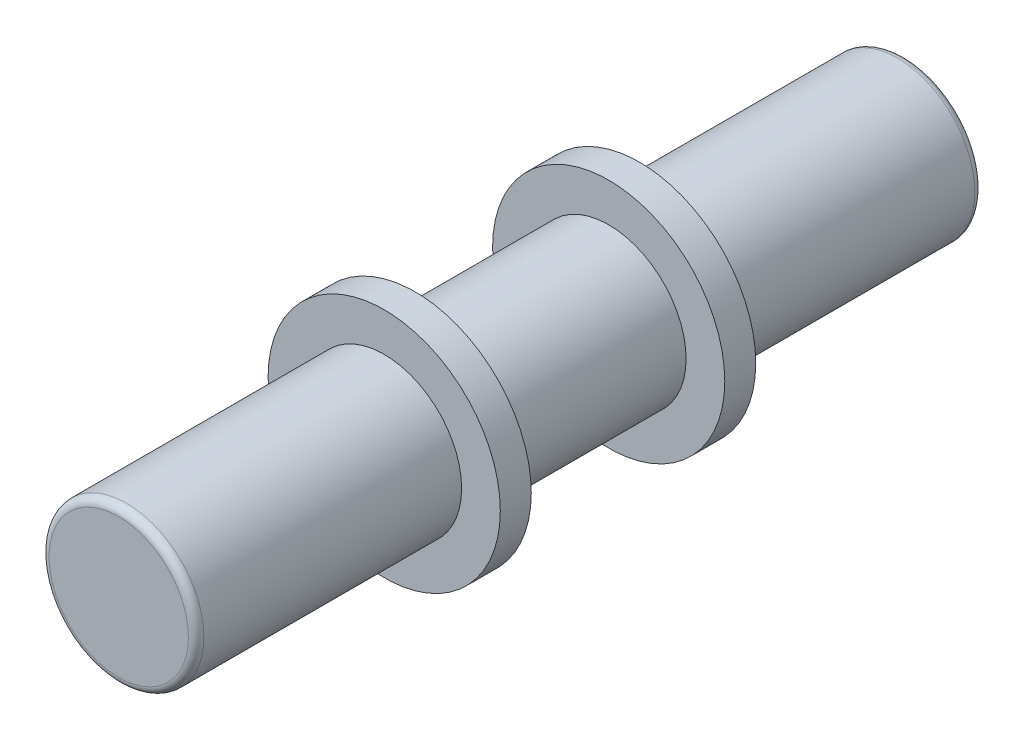
SolidWorks part; units mm, degrees
material "Plain Carbon Steel"
ref_plane "Front Plane" through (0, 0, 0) normal (0, 0, 1) x (1, 0, 0)
ref_plane "Top Plane" through (0, 0, 0) normal (0, 1, 0) x (1, 0, 0)
ref_plane "Right Plane" through (0, 0, 0) normal (1, 0, 0) x (0, 0, -1)
sketch "Sketch2" plane through (0, 0, 0) normal (0, 0, 1) x (1, 0, 0)
  circle A0 centre (0, 0) radius 10
  point P2 (0, 0)
  dimension "D1" = 20
extrude "Boss-Extrude1" add sketch "Sketch2" along normal blind 12.5
sketch "Sketch3" plane through (0, 0, 12.5) normal (0, 0, 1) x (1, 0, 0)
  circle A0 centre (0, 0) radius 15
  point P2 (0, 0)
  dimension "D1" = 30
extrude "Boss-Extrude2" add sketch "Sketch3" along normal blind 4 contours A0
sketch "Sketch4" plane through (0, 0, 16.5) normal (0, 0, 1) x (1, 0, 0)
  circle A0 centre (0, 0) radius 10
  dimension "D1" = 20
extrude "Boss-Extrude3" add sketch "Sketch4" along normal blind 34.3
mirror "Mirror1" about plane through (0, 0, 0) normal (0, 0, 1) of "Boss-Extrude2", "Boss-Extrude3", "Boss-Extrude1"
fillet "Fillet1" radius 1 2 edges at (10, 0, -50.8) (10, 0, 50.8)
